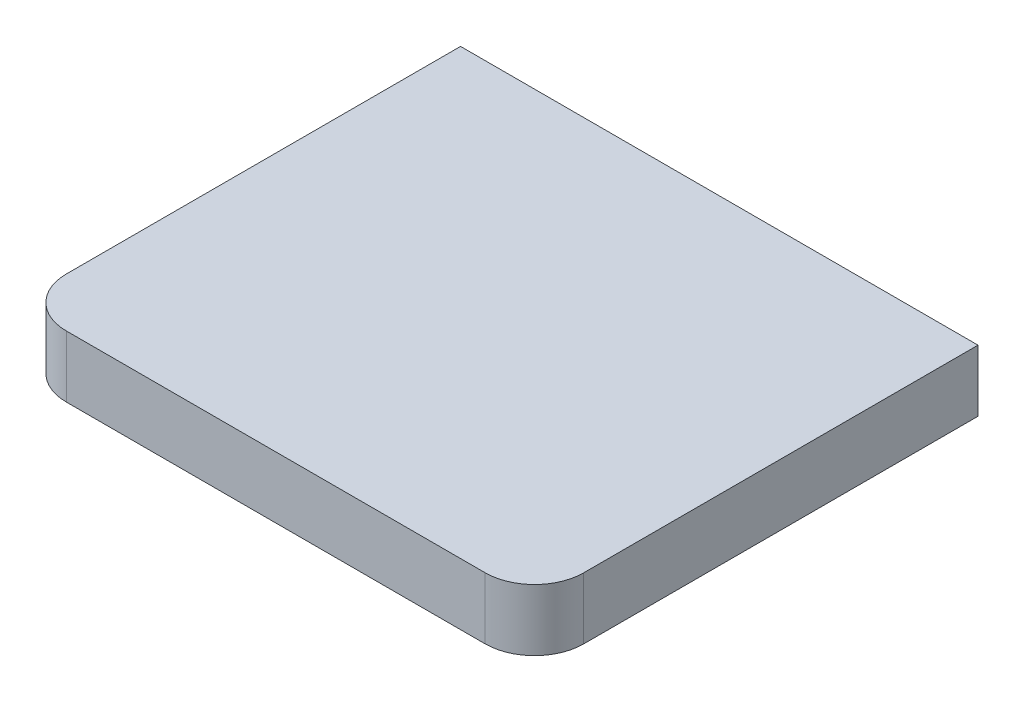
SolidWorks part; units mm, degrees
ref_plane "Front Plane" through (0, 0, 0) normal (0, 0, 1) x (1, 0, 0)
ref_plane "Top Plane" through (0, 0, 0) normal (0, 1, 0) x (1, 0, 0)
ref_plane "Right Plane" through (0, 0, 0) normal (1, 0, 0) x (0, 0, -1)
sketch "Croquis1" plane through (0, 0, 0) normal (0, 1, 0) x (1, 0, 0)
  line L1 (-170, -180) -> (170, -180)
  line L2 (-210, -140) -> (-210, 180)
  line L3 (-210, 180) -> (210, 180)
  line L4 (210, -140) -> (210, 180)
  line L5 (-210, -180) -> (210, 180) construction
  line L6 (-210, 180) -> (210, -180) construction
  arc A0 (170, -180) -> (210, -140) centre (170, -140) ccw
  arc A1 (-170, -180) -> (-210, -140) centre (-170, -140) cw
  point P0 (0, 0)
  dimension "D3" = 40
  dimension "D1" = 420
  dimension "D2" = 360
extrude "Saliente-Extruir1" add sketch "Croquis1" along normal blind 50
sketch "Croquis2" plane through (0, 50, 0) normal (0, 1, 0) x (1, 0, 0)
  line L0 (210, -140) -> (210, 180) construction
  line L1 (-210, 180) -> (210, 180)
  line L2 (-210, 180) -> (-210, 130)
  line L3 (-210, 130) -> (210, 130)
  line L4 (210, 180) -> (210, 130)
  dimension "D1" = 50
sketch "Croquis5" plane through (0, 0, 0) normal (0, -1, 0) x (1, 0, 0)
  line L0 (-170, -180) -> (-170, 192.712) construction
  line L1 (-210, -180) -> (210, -180) construction
  line L2 (-210, -180) -> (-210, 140) construction
  line L3 (-170, 180) -> (170, 180) construction
  line L4 (27.5, 0) -> (-27.5, 0) construction
  line L5 (0, -27.5) -> (0, 27.5) construction
  circle A0 centre (-170, 90) radius 4
  circle A1 centre (-170, -90) radius 4
  circle A2 centre (170, -90) radius 4
  circle A3 centre (170, 90) radius 4
  dimension "D2" = 8
  dimension "D1" = 40
  dimension "D3" = 90
extrude "Cortar-Extruir1" cut sketch "Croquis5" against normal blind 25
